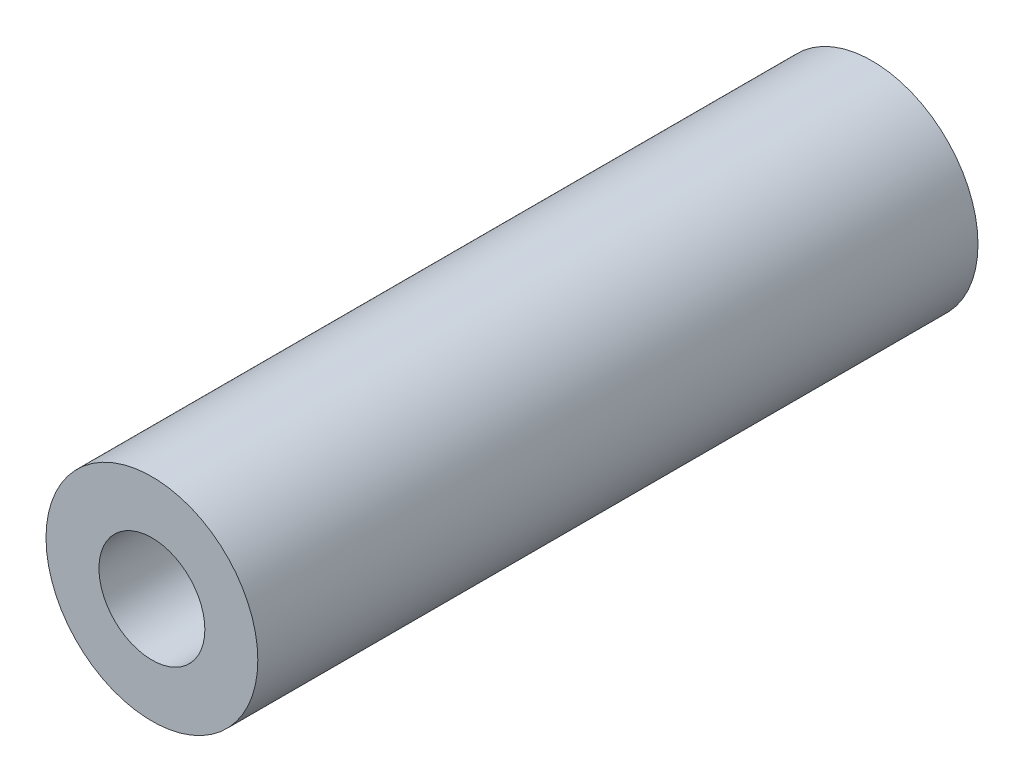
SolidWorks part; units mm, degrees
ref_plane "Front Plane" through (0, 0, 0) normal (0, 0, 1) x (1, 0, 0)
ref_plane "Top Plane" through (0, 0, 0) normal (0, 1, 0) x (1, 0, 0)
ref_plane "Right Plane" through (0, 0, 0) normal (1, 0, 0) x (0, 0, -1)
sketch "Sketch1" plane through (0, 0, 0) normal (0, 0, 1) x (1, 0, 0)
  circle A0 centre (0, 0) radius 12.7
  circle A1 centre (0, 0) radius 6.35
  dimension "D1" = 25.4
  dimension "D2" = 12.7
extrude "Boss-Extrude1" add sketch "Sketch1" against normal blind 86.36
